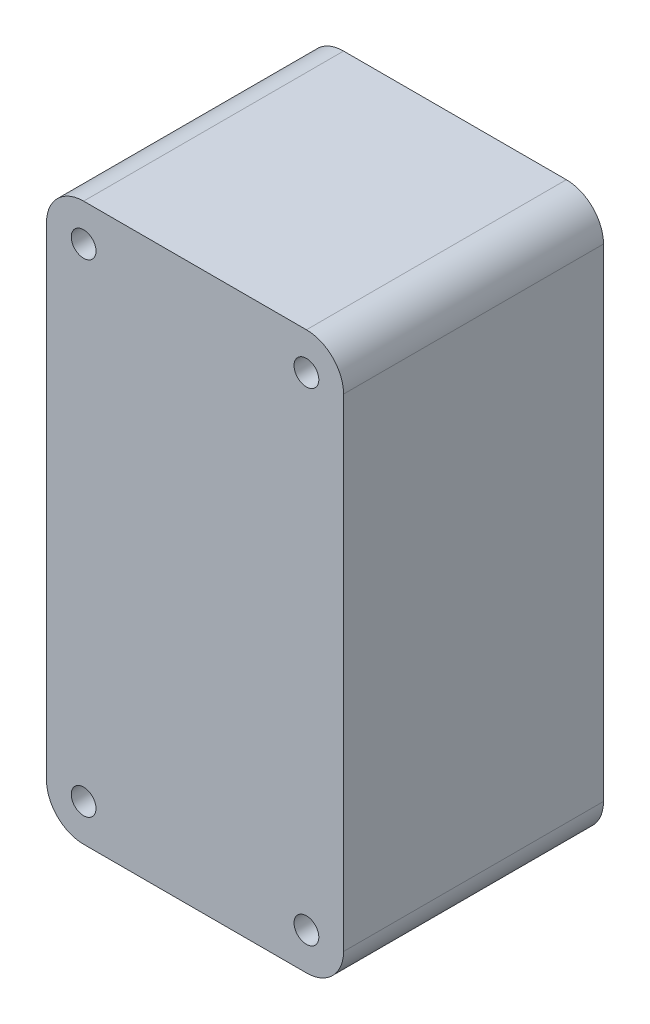
SolidWorks part; units mm, degrees
ref_plane "Plan de face" through (0, 0, 0) normal (0, 0, 1) x (1, 0, 0)
ref_plane "Plan de dessus" through (0, 0, 0) normal (0, 1, 0) x (1, 0, 0)
ref_plane "Plan de droite" through (0, 0, 0) normal (1, 0, 0) x (0, 0, -1)
sketch "Esquisse1" plane through (0, 0, 0) normal (0, 0, 1) x (1, 0, 0)
  line L1 (-28.4193, 4.996) -> (-10.4193, 4.996)
  line L2 (-31.4193, 1.996) -> (-31.4193, -37.004)
  line L3 (-28.4193, -40.004) -> (-10.4193, -40.004)
  line L4 (-7.4193, 1.996) -> (-7.4193, -37.004)
  arc A0 (-28.4193, 4.996) -> (-31.4193, 1.996) centre (-28.4193, 1.996) ccw
  arc A1 (-7.4193, 1.996) -> (-10.4193, 4.996) centre (-10.4193, 1.996) ccw
  arc A2 (-7.4193, -37.004) -> (-10.4193, -40.004) centre (-10.4193, -37.004) cw
  arc A3 (-31.4193, -37.004) -> (-28.4193, -40.004) centre (-28.4193, -37.004) ccw
  dimension "D3" = 3
  dimension "D4" = 3
  dimension "D5" = 3
  dimension "D6" = 3
  dimension "D1" = 24
  dimension "D2" = 45
extrude "Boss.-Extru.1" add sketch "Esquisse1" along normal blind 21
sketch "Esquisse2" plane through (0, 0, 21) normal (0, 0, 1) x (1, 0, 0)
  line L0 (-31.4193, 1.996) -> (-31.4193, -37.004) construction
  line L1 (-28.4193, -40.004) -> (-10.4193, -40.004) construction
  circle A0 centre (-28.4193, -37.004) radius 1
  dimension "D1" = 3
  dimension "D2" = 3
extrude "Enlèv. mat.-Extru.7" cut sketch "Esquisse2" against normal blind 4
sketch "Esquisse6" plane through (0, 0, 21) normal (0, 0, 1) x (1, 0, 0)
  line L0 (-28.4193, -40.004) -> (-10.4193, -40.004) construction
  line L2 (-7.4193, -37.004) -> (-7.4193, 1.996) construction
  circle A0 centre (-10.4193, -37.004) radius 1
  point P6 (-35.5052, -15.5565)
  dimension "D1" = 3
  dimension "D2" = 3
extrude "Enlèv. mat.-Extru.8" cut sketch "Esquisse6" against normal blind 4
sketch "Esquisse7" plane through (0, 0, 21) normal (0, 0, 1) x (1, 0, 0)
  line L0 (-31.4193, 1.996) -> (-31.4193, -37.004) construction
  line L1 (-10.4193, 4.996) -> (-28.4193, 4.996) construction
  circle A0 centre (-28.4193, 1.996) radius 1
  point P6 (-27.6185, 4.186)
  point P9 (-28.1644, 2.5508)
  dimension "D1" = 3
  dimension "D2" = 3
extrude "Enlèv. mat.-Extru.9" cut sketch "Esquisse7" against normal blind 4
sketch "Esquisse8" plane through (0, 0, 21) normal (0, 0, 1) x (1, 0, 0)
  line L0 (-7.4193, -37.004) -> (-7.4193, 1.996) construction
  line L1 (-10.4193, 4.996) -> (-28.4193, 4.996) construction
  circle A0 centre (-10.4193, 1.996) radius 1
  point P6 (-10.6114, 1.0698)
  dimension "D1" = 3
  dimension "D2" = 3
extrude "Enlèv. mat.-Extru.10" cut sketch "Esquisse8" against normal blind 4
